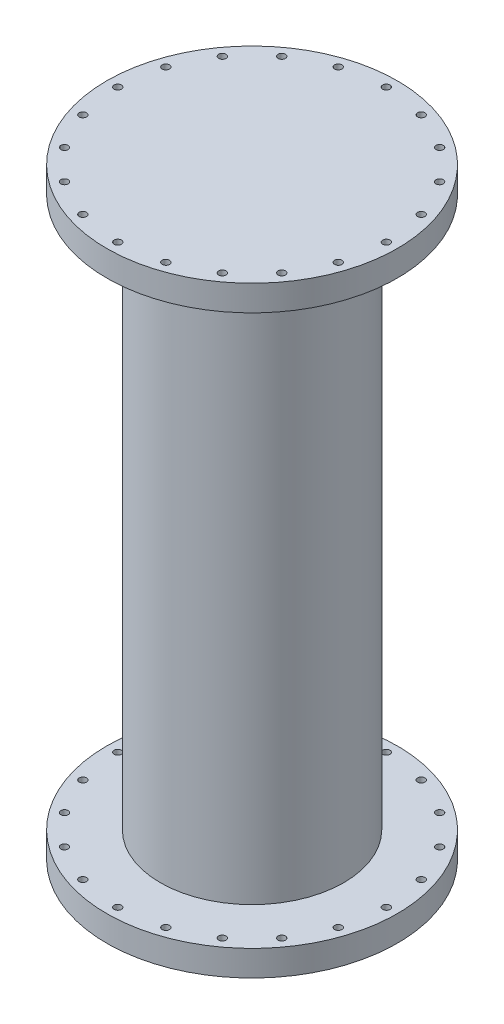
SolidWorks part; units mm, degrees
ref_plane "Plan de face" through (0, 0, 0) normal (0, 0, 1) x (1, 0, 0)
ref_plane "Plan de dessus" through (0, 0, 0) normal (0, 1, 0) x (1, 0, 0)
ref_plane "Plan de droite" through (0, 0, 0) normal (1, 0, 0) x (0, 0, -1)
sketch "Esquisse1" plane through (0, 0, 0) normal (0, 0, 1) x (1, 0, 0)
  line L0 (0, 0) -> (0, -1756.5308) construction
  line L1 (0, 0) -> (396, 0)
  line L2 (0, 0) -> (0, -70)
  line L3 (0, -70) -> (200, -70)
  line L4 (396, 0) -> (396, -70)
  line L26 (250, -70) -> (396, -70)
  line L27 (250, -1570) -> (396, -1570)
  line L29 (200, -70) -> (200, -1570)
  line L31 (250, -70) -> (250, -1570)
  line L32 (0, -1570) -> (200, -1570)
  line L33 (0, -1570) -> (0, -1640)
  line L34 (0, -1640) -> (396, -1640)
  line L35 (396, -1570) -> (396, -1640)
  dimension "D1" = 396
  dimension "D2" = 70
  dimension "D3" = 70
  dimension "D4" = 396
  dimension "D5" = 250
  dimension "D6" = 200
  dimension "D7" = 1500
revolve "Révolution1" add sketch "Esquisse1" angle 360 about L0
sketch "Esquisse2" plane through (0, 0, 0) normal (0, 1, 0) x (1, 0, 0)
  circle A0 centre (366, 0) radius 10
  dimension "D2" = 20
  dimension "D1" = 366
extrude "Enlèv. mat.-Extru.1" cut sketch "Esquisse2" against normal through all
pattern_circular "Répétition circulaire1" count 20 over 360 about axis through (0, 0, 0) along (0, 1, 0) of "Enlèv. mat.-Extru.1"
